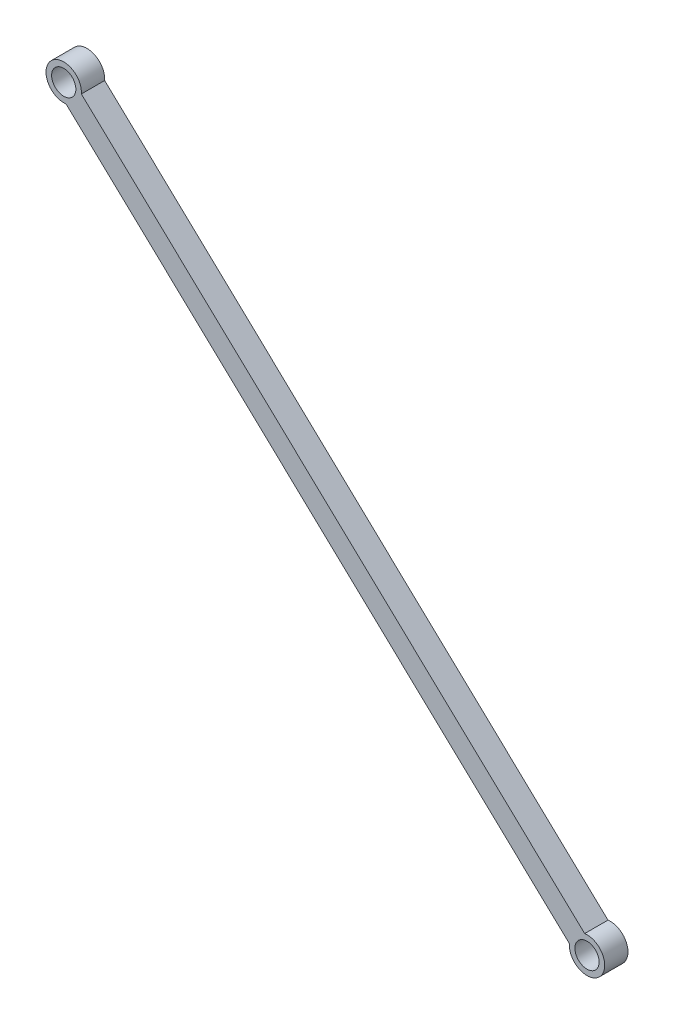
SolidWorks part; units mm, degrees
ref_plane "Front Plane" through (0, 0, 0) normal (0, 0, 1) x (1, 0, 0)
ref_plane "Top Plane" through (0, 0, 0) normal (0, 1, 0) x (1, 0, 0)
ref_plane "Right Plane" through (0, 0, 0) normal (1, 0, 0) x (0, 0, -1)
sketch "Sketch1" plane through (0, 0, 0) normal (0, 0, 1) x (1, 0, 0)
  line L0 (-6.1517, -3.239) -> (-34.2339, 23.2877) construction
  line L1 (-7.0991, -3.1694) -> (-34.1105, 22.3457)
  line L2 (-6.2751, -2.2971) -> (-33.2865, 23.2181)
  arc A0 (-33.2865, 23.2181) -> (-34.1105, 22.3457) centre (-34.2339, 23.2877) ccw
  circle A1 centre (-6.1517, -3.239) radius 0.65
  arc A3 (-7.0991, -3.1694) -> (-6.2751, -2.2971) centre (-6.1517, -3.239) ccw
  circle A5 centre (-34.2339, 23.2877) radius 0.65
  circle A10 centre (-6.1517, -3.239) radius 0.65 construction
  point P3 (0, 0)
  point P5 (-35.6876, 41.2451)
  point P6 (0, 0)
  point P8 (-35.6905, 41.2451)
  point P10 (-34.731, 38.613)
  point P11 (-33.4622, 22.6056)
  dimension "D1" = 1.2
  dimension "D2" = 38.63
extrude "Boss-Extrude1" add sketch "Sketch1" along normal up to surface (1.25 mm away)
